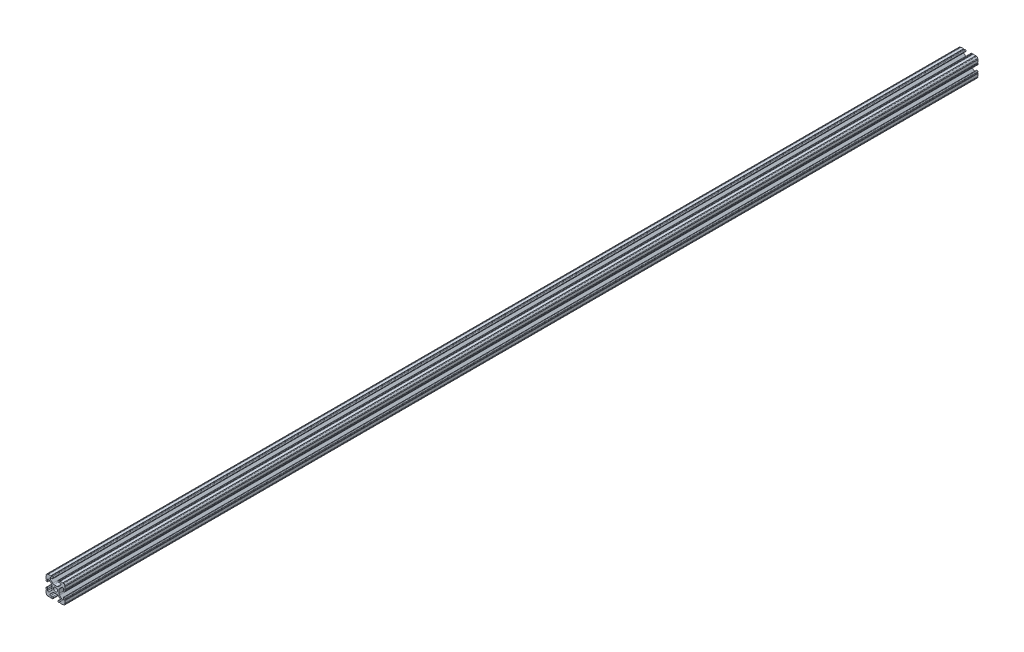
SolidWorks part; units mm, degrees
material "6061 Alloy"
ref_plane "Front Plane" through (0, 0, 0) normal (0, 0, 1) x (1, 0, 0)
ref_plane "Top Plane" through (0, 0, 0) normal (0, 1, 0) x (1, 0, 0)
ref_plane "Right Plane" through (0, 0, 0) normal (1, 0, 0) x (0, 0, -1)
sketch "Sketch2" plane through (0, 0, 0) normal (0, 0, 1) x (1, 0, 0)
  line L0 (0, 12.7) -> (0, -12.7) construction
  line L1 (-12.7, 0) -> (12.7, 0) construction
  line L2 (3.2512, -12.7) -> (12.7, -12.7)
  line L3 (12.7, -12.7) -> (12.7, -3.2512)
  line L4 (3.2512, -12.7) -> (3.2512, -10.4902)
  line L5 (3.2512, -10.4902) -> (8.9276, -10.4902)
  line L6 (8.9276, -10.4902) -> (3.0856, -4.6482)
  line L7 (0, 0) -> (12.7, -12.7) construction
  line L8 (12.7, -3.2512) -> (10.4902, -3.2512)
  line L9 (10.4902, -3.2512) -> (10.4902, -8.9276)
  line L10 (10.4902, -8.9276) -> (4.6482, -3.0856)
  circle A0 centre (0, 0) radius 2.6035
  arc A1 (6.3485, -10.4902) -> (7.1039, -8.6665) centre (6.3485, -9.4219) ccw construction
  point P8 (0, -4.6482)
  dimension "Center Hole Diameter" = 5.207
  dimension "Rail Height" = 25.4
  dimension "Rail Width" = 25.4
  dimension "T-Slot Width" = 6.5024
  dimension "Slot Inner Width" = 14.8336
  dimension "Thickness" = 2.2098
  dimension "Slot Depth" = 5.842
  dimension "D1" = 2.2098
sketch "Sketch3" plane through (0, 0, 0) normal (1, 0, 0) x (0, 0, -1)
  line L0 (-609.6, -12.7) -> (609.6, -12.7) construction
  line L1 (-584.2, 0) -> (584.2, 0) construction
  dimension "Length" = 1219.2
  dimension "D1" = 25.4
sketch "Sketch4" plane through (0, 0, 0) normal (0, 0, 1) x (1, 0, 0)
  line L0 (4.1904, -12.7) -> (10.1173, -12.7)
  line L1 (3.2512, -12.7) -> (12.7, -12.7) construction
  line L2 (3.2512, -12.7) -> (3.2512, -10.4902) construction
  line L3 (3.2512, -10.4902) -> (8.9276, -10.4902) construction
  line L4 (3.2512, -11.4294) -> (3.2512, -11.7608)
  line L5 (4.1904, -10.4902) -> (6.3485, -10.4902)
  line L6 (0, -4.6482) -> (2.164, -4.6482)
  line L7 (8.9276, -10.4902) -> (3.0856, -4.6482) construction
  line L8 (3.7373, -5.2999) -> (7.1039, -8.6665)
  line L9 (12.7, -12.7) -> (12.7, -3.2512) construction
  line L10 (10.4902, -8.9276) -> (4.6482, -3.0856) construction
  line L11 (10.4902, -3.2512) -> (10.4902, -8.9276) construction
  line L12 (10.4902, -6.3485) -> (10.4902, -4.1904)
  line L13 (12.7, -3.2512) -> (10.4902, -3.2512) construction
  line L14 (11.4294, -3.2512) -> (11.7608, -3.2512)
  line L15 (12.7, -4.1904) -> (12.7, -10.1173)
  line L16 (8.6665, -7.1039) -> (5.2999, -3.7373)
  line L17 (4.6482, 0) -> (4.6482, -2.164)
  line L18 (-12.7, 0) -> (12.7, 0) construction
  line L19 (0, -4.6482) -> (0, -2.6035)
  line L20 (0, 12.7) -> (0, -12.7) construction
  line L21 (4.6482, 0) -> (2.6035, 0)
  arc A0 (3.2512, -11.7608) -> (4.1904, -12.7) centre (4.1904, -11.7608) ccw
  arc A2 (3.2512, -11.4294) -> (4.1904, -10.4902) centre (4.1904, -11.4294) cw
  arc A3 (6.3485, -10.4902) -> (7.1039, -8.6665) centre (6.3485, -9.4219) ccw
  arc A4 (2.164, -4.6482) -> (3.7373, -5.2999) centre (2.164, -6.8732) cw
  arc A5 (10.1173, -12.7) -> (12.7, -10.1173) centre (10.1173, -10.1173) ccw
  arc A6 (8.6665, -7.1039) -> (10.4902, -6.3485) centre (9.4219, -6.3485) ccw
  arc A7 (10.4902, -4.1904) -> (11.4294, -3.2512) centre (11.4294, -4.1904) cw
  arc A8 (11.7608, -3.2512) -> (12.7, -4.1904) centre (11.7608, -4.1904) cw
  arc A9 (5.2999, -3.7373) -> (4.6482, -2.164) centre (6.8732, -2.164) cw
  circle A10 centre (0, 0) radius 2.6035 construction
  arc A11 (0, -2.6035) -> (2.6035, 0) centre (0, 0) ccw
  dimension "D1" = 2.5827
  dimension "D2" = 2.225
  dimension "D3" = 0.9392
extrude "Boss-Extrude1" add sketch "Sketch4" along normal mid plane 1219.2
sketch "Sketch5" plane through (0, 0, 0) normal (0, 0, 1) x (1, 0, 0)
  line L0 (3.2512, -12.7) -> (12.7, -12.7) construction
  line L1 (4.1904, -10.4902) -> (6.3485, -10.4902) construction
  line L3 (0, 0) -> (12.7, -12.7) construction
  line L4 (6.3485, -10.4902) -> (6.3485, -12.7) construction
  line L5 (8.9276, -10.4902) -> (3.0856, -4.6482) construction
  circle A0 centre (10.3562, -12.7) radius 0.5524
  circle A1 centre (5.796, -12.7) radius 0.5524
  circle A2 centre (12.7, -10.3562) radius 0.5524
  circle A3 centre (12.7, -5.796) radius 0.5524
  point P10 (5.2694, -10.4902)
  point P12 (9.4219, -6.3485)
  dimension "D1" = 1.1049
extrude "Cut-Extrude1" cut sketch "Sketch5" against normal through all both and the other way through all
mirror "Mirror1" about plane through (0, 0, 0) normal (1, 0, 0) of bodies 137 134
mirror "Mirror2" about plane through (0, 0, 0) normal (0, 1, 0) of bodies 135
equation "\"D1@Boss-Extrude1\"=\"Length@Sketch3\""
equation "\"D1@Sketch2\"=\"Thickness@Sketch2\""
equation "\"D2@Sketch4\"=\"Slot Inner Width@Sketch2\"*0.15"
equation "\"D1@Sketch4\"=\"D3@Sketch4\"*2.75"
equation "\"D3@Sketch4\"=\"Thickness@Sketch2\"*0.425"
equation "\"D1@Sketch5\"=\"Thickness@Sketch2\"*0.5"
